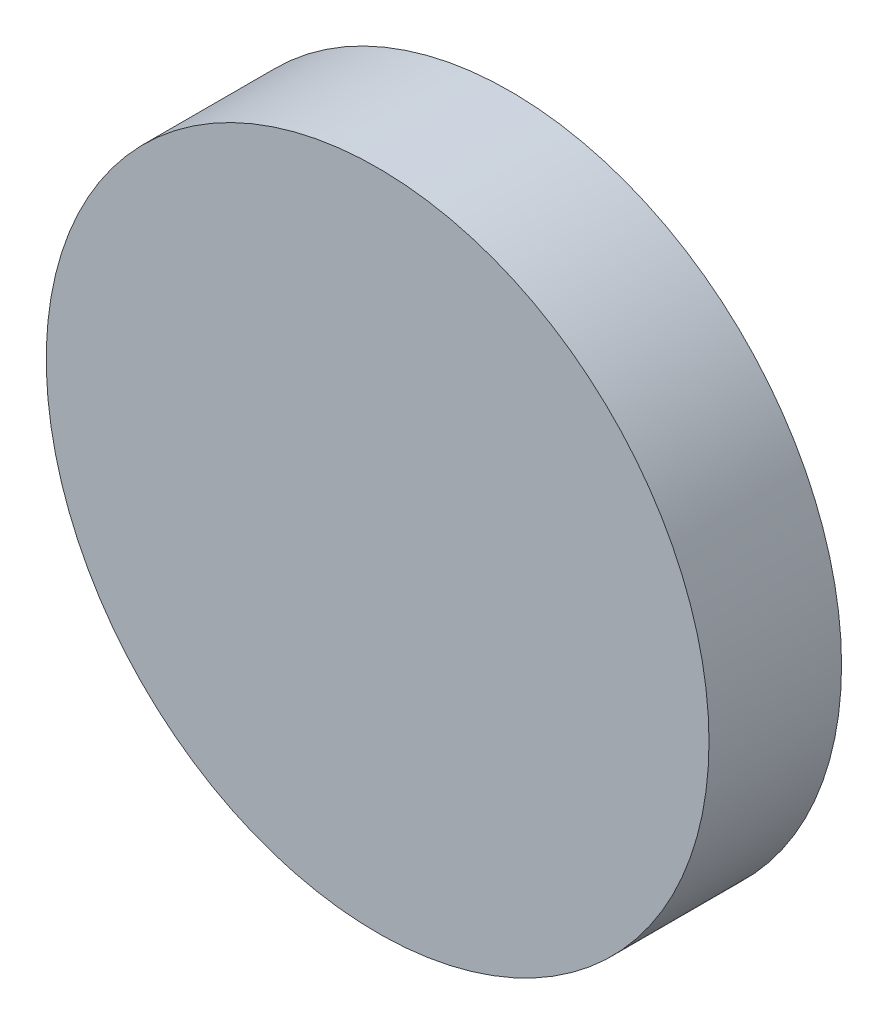
SolidWorks part; units mm, degrees
ref_plane "Plan de face" through (0, 0, 0) normal (0, 0, 1) x (1, 0, 0)
ref_plane "Plan de dessus" through (0, 0, 0) normal (0, 1, 0) x (1, 0, 0)
ref_plane "Plan de droite" through (0, 0, 0) normal (1, 0, 0) x (0, 0, -1)
sketch "Esquisse1" plane through (0, 0, 0) normal (0, 0, 1) x (1, 0, 0)
  circle A0 centre (0, 0) radius 12.7
extrude "Boss.-Extru.1" add sketch "Esquisse1" along normal mid plane 5.08
